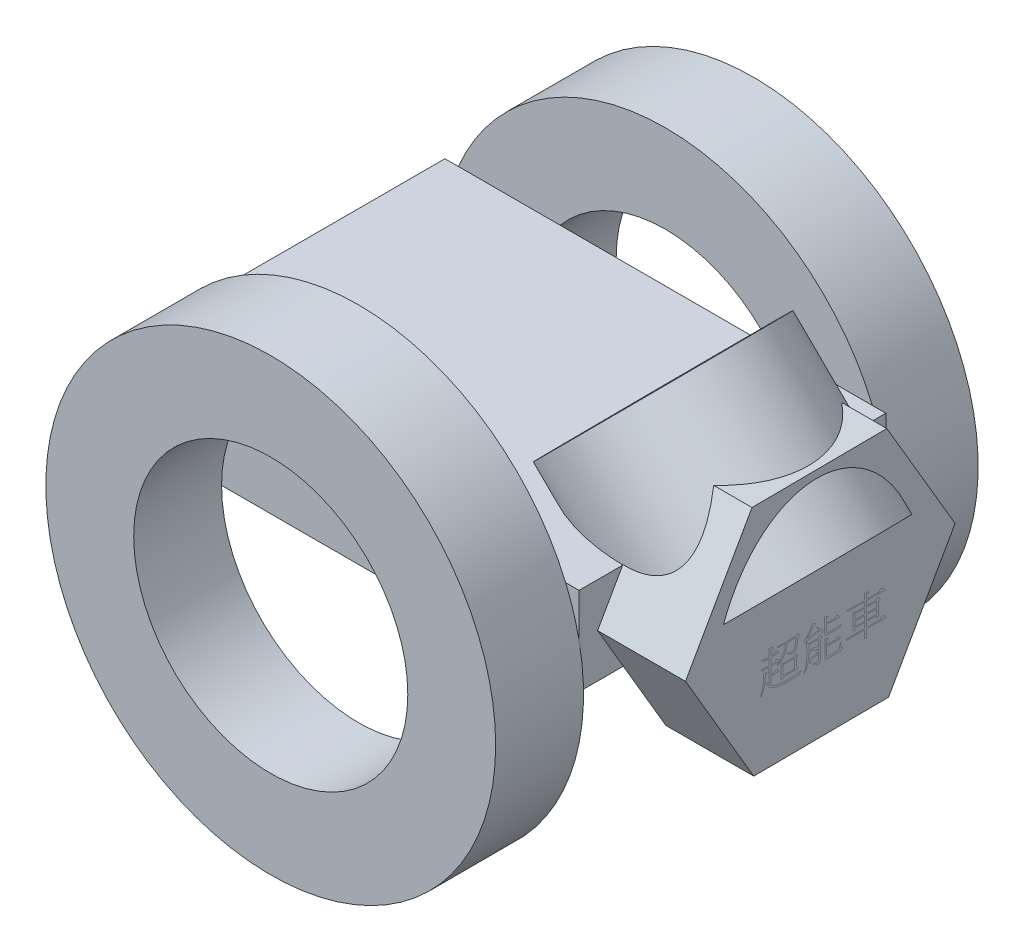
SolidWorks part; units mm, degrees
ref_plane "前基準面" through (0, 0, 0) normal (0, 0, 1) x (1, 0, 0)
ref_plane "上基準面" through (0, 0, 0) normal (0, 1, 0) x (1, 0, 0)
ref_plane "右基準面" through (0, 0, 0) normal (1, 0, 0) x (0, 0, -1)
sketch "草圖1" plane through (0, 0, 0) normal (0, 1, 0) x (1, 0, 0)
  line L1 (-25.0858, 17.4566) -> (25.0858, 17.4566)
  line L2 (-25.0858, 17.4566) -> (-25.0858, -17.4566)
  line L3 (-25.0858, -17.4566) -> (25.0858, -17.4566)
  line L4 (25.0858, 17.4566) -> (25.0858, -17.4566)
  line L5 (-25.0858, 17.4566) -> (25.0858, -17.4566) construction
  line L6 (-25.0858, -17.4566) -> (25.0858, 17.4566) construction
  point P0 (0, 0)
extrude "填料-伸長1" add sketch "草圖1" along normal blind 10
sketch "草圖2" plane through (0, 0, 17.4566) normal (0, 0, 1) x (1, 0, 0)
  circle A0 centre (0, 0) radius 15.5969
extrude "伸長-薄件1" add sketch "草圖2" along normal blind 10 thin
sketch "草圖3" plane through (0, 0, -17.4566) normal (0, 0, -1) x (-1, 0, 0)
  line L0 (-25.0858, 0) -> (25.0858, 0) construction
  circle A0 centre (0, 0) radius 15.5969
extrude "伸長-薄件2" add sketch "草圖3" along normal blind 10 thin
sketch "草圖4" plane through (25.0858, 0, 0) normal (1, 0, 0) x (0, 0, -1)
  line L0 (-1017.4566, 5.0896) -> (48982.5434, 5.0896) construction
  line L2 (7.7675, -8.1423) -> (15.3429, 5.2005)
  line L3 (15.3429, 5.2005) -> (7.5754, 18.4324)
  line L4 (7.5754, 18.4324) -> (-7.7675, 18.3214)
  line L5 (-7.7675, 18.3214) -> (-15.3429, 4.9786)
  line L6 (-15.3429, 4.9786) -> (-7.5754, -8.2532)
  line L7 (-7.5754, -8.2532) -> (7.7675, -8.1423)
  circle A0 centre (0, 5.0896) radius 13.2877 construction
extrude "填料-伸長2" add sketch "草圖4" along normal blind 10
ref_plane "平面1" through (8.3543, -8.3541, -0.0604) normal (0.7071, -0.7071, -0.0051) x (-0.0036, 0.0036, -1)
sketch "草圖5" plane through (8.3543, -8.3541, -0.0604) normal (0.7071, -0.7071, -0.0051) x (-0.0036, 0.0036, -1)
  circle A0 centre (-0.423, 25.101) radius 12.0973
extrude "填料-伸長3" add sketch "草圖5" along normal blind 7 and the other way blind 12
sketch "草圖6" plane through (13.3041, -13.3037, -0.0962) normal (0.7071, -0.7071, -0.0051) x (-0.0036, 0.0036, -1)
  line L0 (-8.903, 31.3585) -> (8.1257, 31.3585)
  spline S0 degree 2 poles (8.1257, 31.3585) (-0.3886, 41.8541) (-8.903, 31.3585) knots 0 0 0 1 1 1
extrude "除料-伸長1" cut sketch "草圖6" against normal through all
ref_plane "平面2" through (45.0858, 0, 0) normal (1, 0, 0) x (0, 0, -1)
sketch "草圖7" plane through (45.0858, 0, 0) normal (1, 0, 0) x (0, 0, -1)
  text T0 "超能車"
split line "分割線1"
